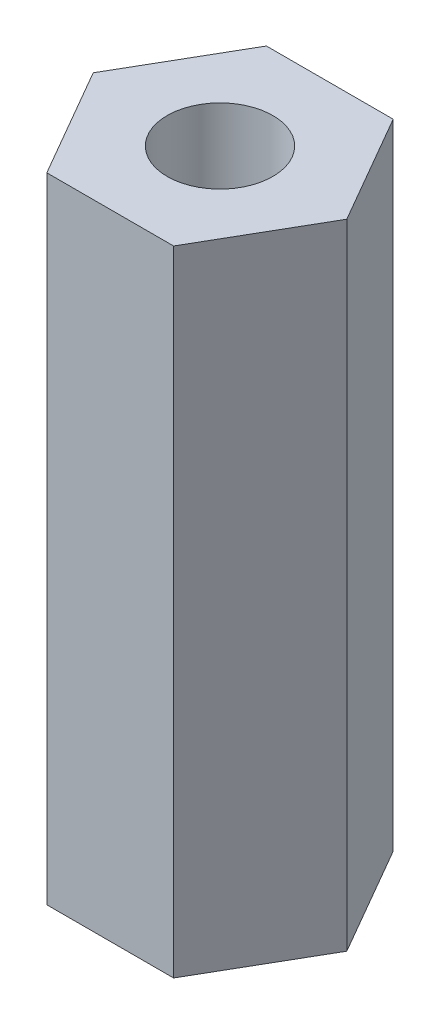
SolidWorks part; units mm, degrees
ref_plane "前视基准面" through (0, 0, 0) normal (0, 0, 1) x (1, 0, 0)
ref_plane "上视基准面" through (0, 0, 0) normal (0, 1, 0) x (1, 0, 0)
ref_plane "右视基准面" through (0, 0, 0) normal (1, 0, 0) x (0, 0, -1)
sketch "草图1" plane through (0, 0, 0) normal (0, 1, 0) x (1, 0, 0)
  line L1 (1.5, 2.5981) -> (-1.5, 2.5981)
  line L2 (-1.5, 2.5981) -> (-3, 0)
  line L3 (-3, 0) -> (-1.5, -2.5981)
  line L4 (-1.5, -2.5981) -> (1.5, -2.5981)
  line L5 (1.5, -2.5981) -> (3, 0)
  line L6 (3, 0) -> (1.5, 2.5981)
  circle A0 centre (0, 0) radius 2.5981 construction
  dimension "D1" = 3
extrude "凸台-拉伸1" add sketch "草图1" along normal blind 15
hole_wizard "M3 螺纹孔1" positions "草图2" profile "草图3" tap size "M3" standard "GB" end condition through all
sketch "草图2" plane through (0, 15, 0) normal (0, 1, 0) x (1, 0, 0)
  point P0 (0, 0)
sketch "草图3" plane through (0, 15, 0) normal (1, 0, 0) x (0, 0, 1)
  line L0 (0, 0) -> (0, 15)
  line L1 (0, 15) -> (1.25, 15)
  line L2 (1.25, 15) -> (1.25, 0)
  line L5 (1.25, 0) -> (0, 0)
  line L11 (0, -6.35) -> (0, 107.95) construction
  dimension "通孔螺纹孔钻头直径" = 2.5
  dimension "通孔螺纹孔钻头深度" = 15
cosmetic thread "孔螺蚊线1"
